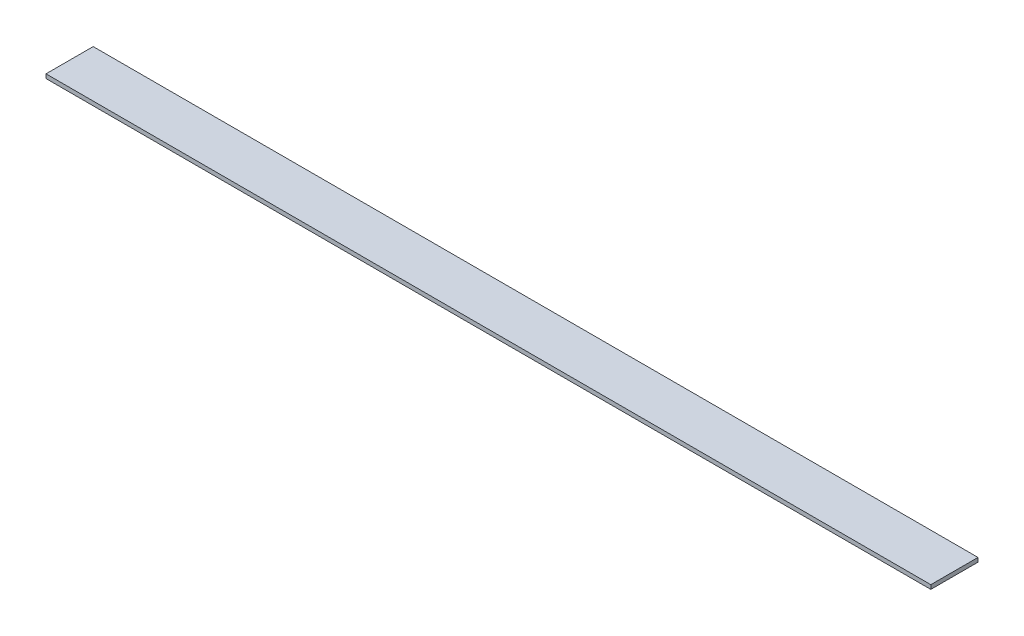
SolidWorks part; units mm, degrees
ref_plane "Vorne" through (0, 0, 0) normal (0, 0, 1) x (1, 0, 0)
ref_plane "Oben" through (0, 0, 0) normal (0, 1, 0) x (1, 0, 0)
ref_plane "Rechts" through (0, 0, 0) normal (1, 0, 0) x (0, 0, -1)
ref_plane "E_Boden" through (0, 1, 0) normal (0, 1, 0) x (1, 0, 0)
sketch "Skizze1" plane through (0, 0, 0) normal (0, 1, 0) x (1, 0, 0)
  line L0 (0, 0) -> (-118.8274, 0) construction
  line L1 (-118.8274, 0) -> (167.8176, 0) construction
  line L2 (0, 0) -> (0, 71.7915) construction
  line L3 (0, 71.7915) -> (0, -82.215) construction
  line L5 (-750, 40) -> (750, 40)
  line L6 (-750, 40) -> (-750, -40)
  line L7 (-750, -40) -> (750, -40)
  line L8 (750, 40) -> (750, -40)
  dimension "D1" = 80
  dimension "D2" = 1500
extrude "Aufsatz-Linear austragen1" add sketch "Skizze1" along normal blind 7
